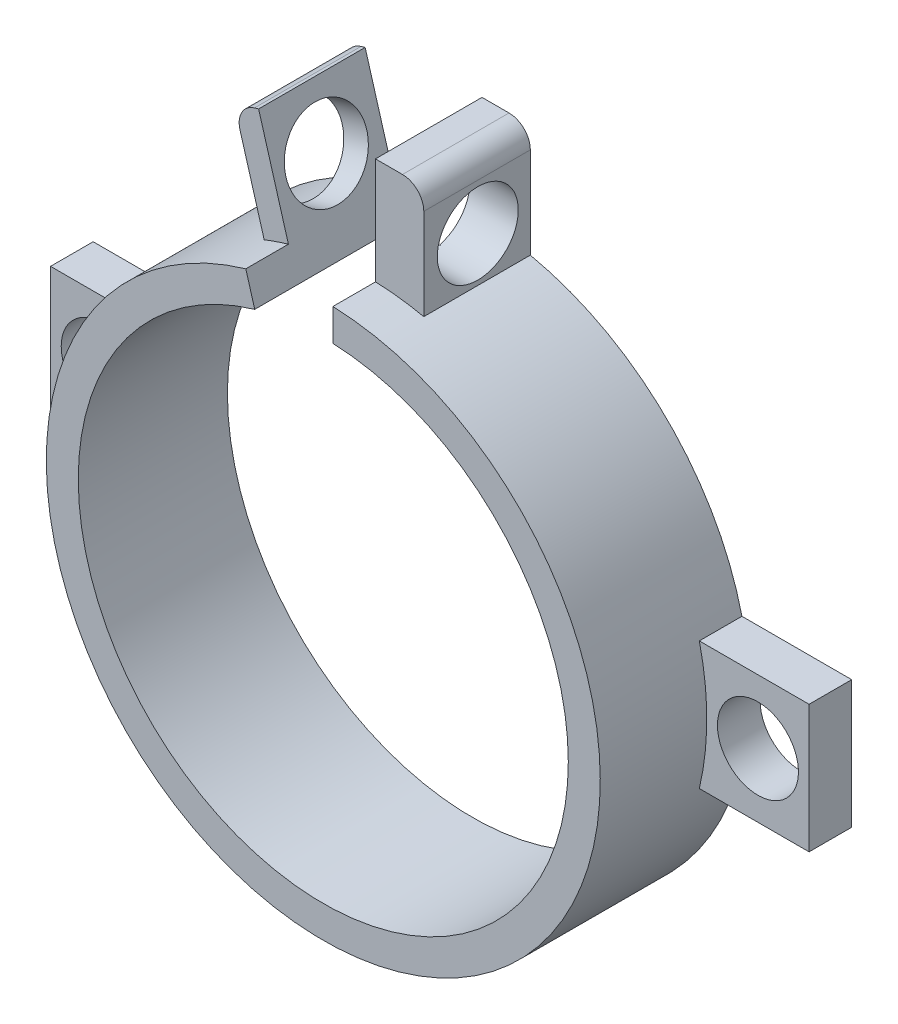
SolidWorks part; units mm, degrees
ref_plane "Front Plane" through (0, 0, 0) normal (0, 0, 1) x (1, 0, 0)
ref_plane "Top Plane" through (0, 0, 0) normal (0, 1, 0) x (1, 0, 0)
ref_plane "Right Plane" through (0, 0, 0) normal (1, 0, 0) x (0, 0, -1)
sketch "Sketch1" plane through (0, 0, 0) normal (0, 0, 1) x (1, 0, 0)
  line L0 (-3.6363, 12.4811) -> (-3.2167, 11.041)
  line L1 (0.4496, 12.9922) -> (0.4496, 11.4912)
  arc A0 (-3.2167, 11.041) -> (0.4496, 11.4912) centre (0, 0) ccw
  arc A1 (-3.6363, 12.4811) -> (0.4496, 12.9922) centre (0, 0) ccw
  dimension "D1" = 23
  dimension "D2" = 26
extrude "Boss-Extrude1" add sketch "Sketch1" against normal blind 7
sketch "Sketch2" plane through (0, 0, -7) normal (0, 0, -1) x (-1, 0, 0)
  line L0 (0, 0) -> (0, 18.6307) construction
  line L1 (0, 0) -> (-11.8401, 0) construction
  line L2 (-11.8401, -3) -> (-17.8, -3)
  line L9 (-11.8401, 3) -> (-11.8401, -3)
  line L12 (-17.8, -3) -> (-17.8, 3)
  line L13 (-17.8, 3) -> (-11.8401, 3)
  line L14 (-13, -4.0058) -> (-13, 4.4848)
  line L16 (13, -4.0058) -> (13, 4.4848)
  line L17 (17.8, -3) -> (17.8, 3)
  line L18 (17.8, 3) -> (11.8401, 3)
  line L19 (11.8401, 3) -> (11.8401, -3)
  line L20 (11.8401, -3) -> (17.8, -3)
  circle A0 centre (-15.4, 0) radius 1.9
  arc A1 (3, 12.6491) -> (-6.9282, -11) centre (0, 0) ccw construction
  circle A2 centre (15.4, 0) radius 1.9
  arc M24 (-0.4496, 12.9922) -> (3.6363, 12.4811) centre (0, 0) ccw
  dimension "D2" = 3.8
  dimension "D1" = 90
  dimension "D3" = 3
  dimension "D4" = 3
  dimension "D5" = 2.4
  dimension "D6" = 2.4
extrude "Boss-Extrude2" add sketch "Sketch2" against normal blind 2 contours L16 L20 L17 L18 A2 | L20 L16 M24 | L16 L18 M24 | L2 L14 L13 L12 A0 | L14 L2 M24 | L14 L13 M24
sketch "Sketch3" plane through (0, 0, -7) normal (0, 0, -1) x (-1, 0, 0)
  line L0 (-3.571, 12.85) -> (2.7326, 13.1389) construction
  line L1 (-0.4496, 12.9922) -> (-0.4496, 11.4912) construction
  line L2 (-2.7175, 13) -> (-0.4496, 13)
  line L3 (-2.7175, 13) -> (-2.7175, 16.9922)
  line L4 (-1.7175, 17.9922) -> (-0.4496, 17.9922)
  line L5 (-0.4496, 13) -> (-0.4496, 17.9922)
  line L6 (-2.7175, 13) -> (-2.7175, 12.1704)
  line L7 (-2.7175, 12.1704) -> (-0.4496, 12.1704)
  line L8 (-0.4496, 12.1704) -> (-0.4496, 13)
  arc A0 (-0.4496, 12.9922) -> (-12.6491, 3) centre (0, 0) ccw construction
  arc A1 (-1.7175, 17.9922) -> (-2.7175, 16.9922) centre (-1.7175, 16.9922) ccw
  arc M11 (-0.4496, 12.9922) -> (-12.6491, 3) centre (0, 0) ccw
  dimension "D1" = 1
  dimension "D2" = 5
  dimension "D3" = 2.2679
extrude "Boss-Extrude3" add sketch "Sketch3" against normal blind 5 contours L4 A1 L3 L2 L5 | L0 L6 M11 | L6 L0 L8 L2
sketch "Sketch4" plane through (2.7175, 0, 0) normal (1, 0, 0) x (0, 0, -1)
  circle A0 centre (4.5339, 14.8308) radius 1.9
  point P6 (4.5339, 14.8308)
  dimension "D1" = 3.8
extrude "Cut-Extrude1" cut sketch "Sketch4" against normal blind 5
sketch "Sketch5" plane through (0, 0, -7) normal (0, 0, -1) x (-1, 0, 0)
  line L0 (3.2116, 12.9052) -> (8.2476, 10.4333) construction
  line L1 (3.4265, 11.761) -> (5.0349, 17.2815)
  line L2 (3.2167, 11.041) -> (3.6363, 12.4811) construction
  line L3 (5.0349, 17.2815) -> (5.2269, 17.2255)
  line L4 (5.9073, 15.9857) -> (4.4969, 11.1448)
  line L5 (4.4969, 11.1448) -> (3.4265, 11.761)
  line L7 (5.0349, 17.2815) -> (3.6363, 12.4811)
  arc A0 (12.6491, 3) -> (3.6363, 12.4811) centre (0, 0) ccw construction
  arc A1 (5.9073, 15.9857) -> (5.2269, 17.2255) centre (4.9472, 16.2655) ccw
  arc M7 (12.6491, 3) -> (3.6363, 12.4811) centre (0, 0) ccw
  dimension "D1" = 1
  dimension "D2" = 5
  dimension "D3" = 1.2
extrude "Boss-Extrude4" add sketch "Sketch5" against normal blind 5 contours L7 L0 L4 A1 L3 | L0 L1 L4 M7
sketch "Sketch6" plane through (-1.1521, -0.3357, 0) normal (-0.9601, -0.2797, 0) x (0, 0, 1)
  circle A0 centre (-4.4122, 15.2621) radius 1.9
  point P2 (-4.4122, 15.2621)
  dimension "D1" = 3.8
extrude "Cut-Extrude2" cut sketch "Sketch6" against normal blind 4
